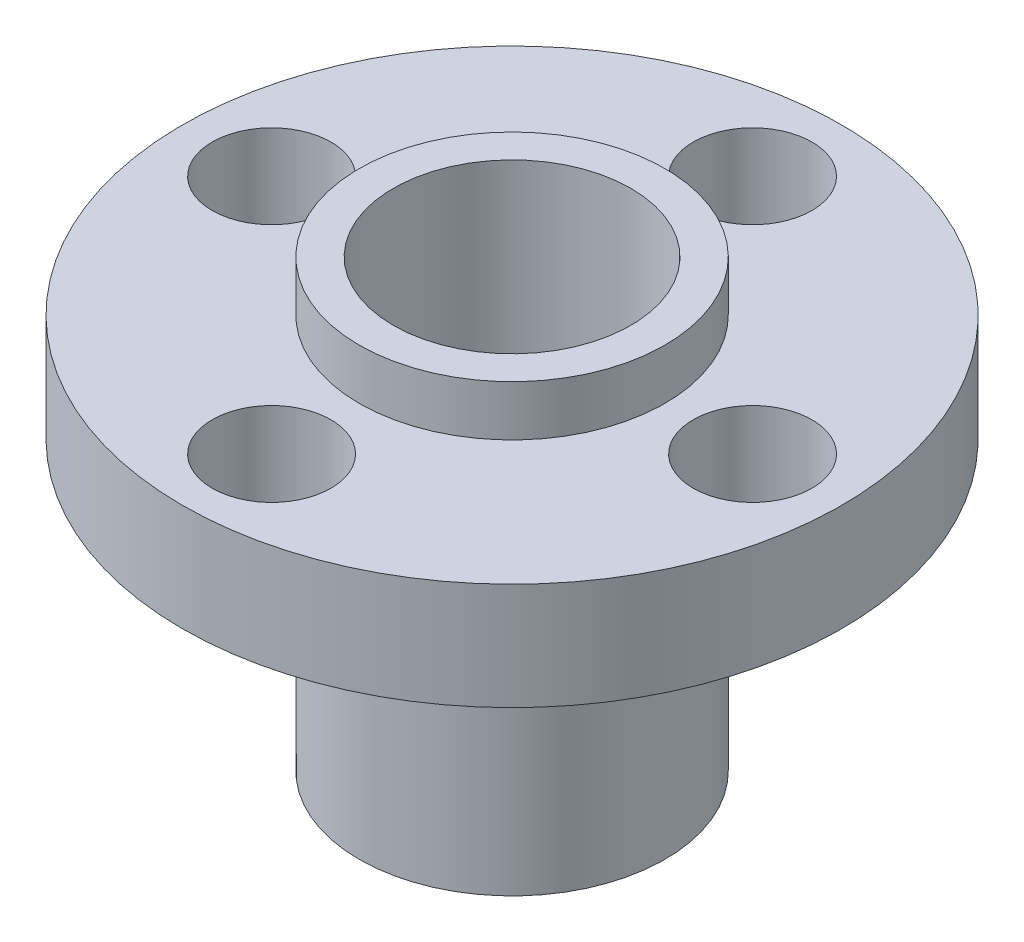
SolidWorks part; units mm, degrees
ref_plane "Front Plane" through (0, 0, 0) normal (0, 0, 1) x (1, 0, 0)
ref_plane "Top Plane" through (0, 0, 0) normal (0, 1, 0) x (1, 0, 0)
ref_plane "Right Plane" through (0, 0, 0) normal (1, 0, 0) x (0, 0, -1)
sketch "Sketch1" plane through (0, 0, 0) normal (0, 1, 0) x (1, 0, 0)
  circle A0 centre (0, 0) radius 11.1
  dimension "D1" = 22.2
extrude "Boss-Extrude1" add sketch "Sketch1" along normal blind 3.6
sketch "Sketch2" plane through (0, 3.6, 0) normal (0, 1, 0) x (1, 0, 0)
  circle A0 centre (0, 0) radius 5.15
  dimension "D1" = 10.3
extrude "Boss-Extrude2" add sketch "Sketch2" along normal blind 1.7 and the other way blind 13.3
sketch "Sketch3" plane through (0, 5.3, 0) normal (0, 1, 0) x (1, 0, 0)
  line L0 (0, 11.1) -> (0, -11.1) construction
  line L1 (0, -11.1) -> (-11.1, 0) construction
  line L2 (-11.1, 0) -> (11.1, 0) construction
  line L3 (-5.55, -5.55) -> (0, 0) construction
  circle A0 centre (0, 0) radius 4
  circle A1 centre (0, 0) radius 11.1 construction
  circle A2 centre (-8.1, 0) radius 2
  circle A3 centre (8.1, 0) radius 2
  circle A4 centre (0, 8.1) radius 2
  circle A5 centre (0, -8.1) radius 2
  dimension "D1" = 8
  dimension "D2" = 3
  dimension "D3" = 4
extrude "Cut-Extrude1" cut sketch "Sketch3" against normal through all
